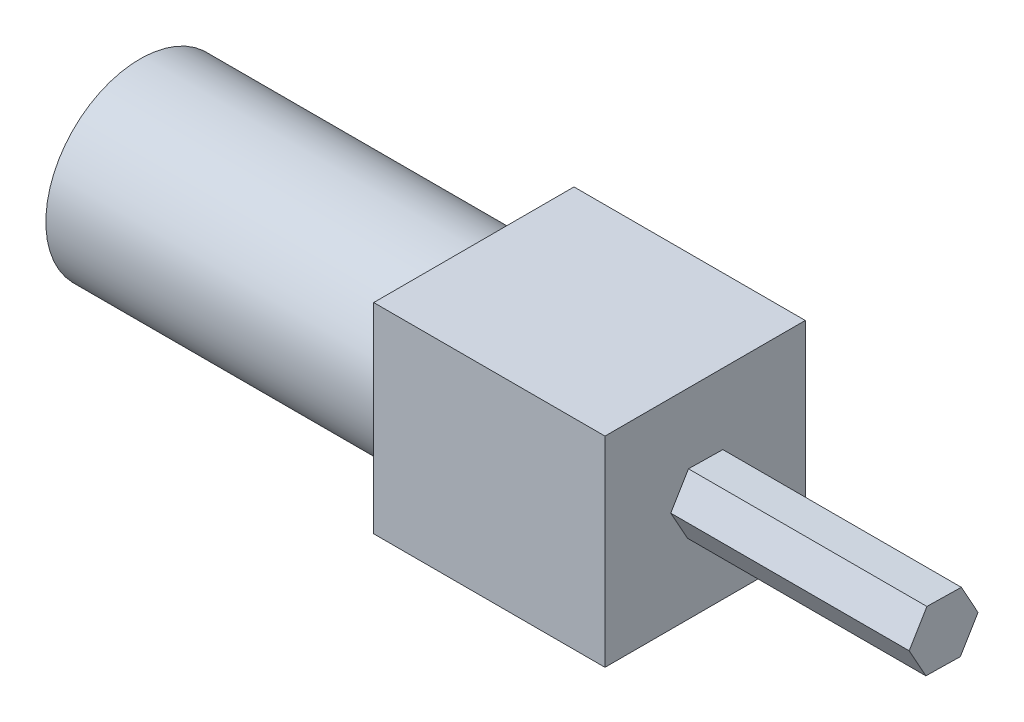
SolidWorks part; units mm, degrees
ref_plane "Front Plane" through (0, 0, 0) normal (0, 0, 1) x (1, 0, 0)
ref_plane "Top Plane" through (0, 0, 0) normal (0, 1, 0) x (1, 0, 0)
ref_plane "Right Plane" through (0, 0, 0) normal (1, 0, 0) x (0, 0, -1)
sketch "Sketch1" plane through (0, 0, 0) normal (1, 0, 0) x (0, 0, -1)
  circle A0 centre (0, 0) radius 20.066
  dimension "D1" = 40.132
extrude "Boss-Extrude1" add sketch "Sketch1" along normal blind 71.12
sketch "Sketch2" plane through (71.12, 0, 0) normal (1, 0, 0) x (0, 0, -1)
  line L1 (-21.336, 21.336) -> (21.336, 21.336)
  line L2 (-21.336, 21.336) -> (-21.336, -21.336)
  line L3 (-21.336, -21.336) -> (21.336, -21.336)
  line L4 (21.336, 21.336) -> (21.336, -21.336)
  line L5 (-21.336, 21.336) -> (21.336, -21.336) construction
  line L6 (-21.336, -21.336) -> (21.336, 21.336) construction
  point P0 (0, 0)
  dimension "D1" = 42.672
  dimension "D2" = 42.672
extrude "Boss-Extrude2" add sketch "Sketch2" along normal blind 49.276
sketch "Sketch3" plane through (120.396, 0, 0) normal (1, 0, 0) x (0, 0, -1)
  line L1 (3.5562, -6.4122) -> (7.3313, -0.1263)
  line L2 (7.3313, -0.1263) -> (3.775, 6.2859)
  line L3 (3.775, 6.2859) -> (-3.5562, 6.4122)
  line L4 (-3.5562, 6.4122) -> (-7.3313, 0.1263)
  line L5 (-7.3313, 0.1263) -> (-3.775, -6.2859)
  line L6 (-3.775, -6.2859) -> (3.5562, -6.4122)
  circle A0 centre (0, 0) radius 6.35 construction
  dimension "D1" = 12.7
extrude "Boss-Extrude3" add sketch "Sketch3" along normal blind 50.8
